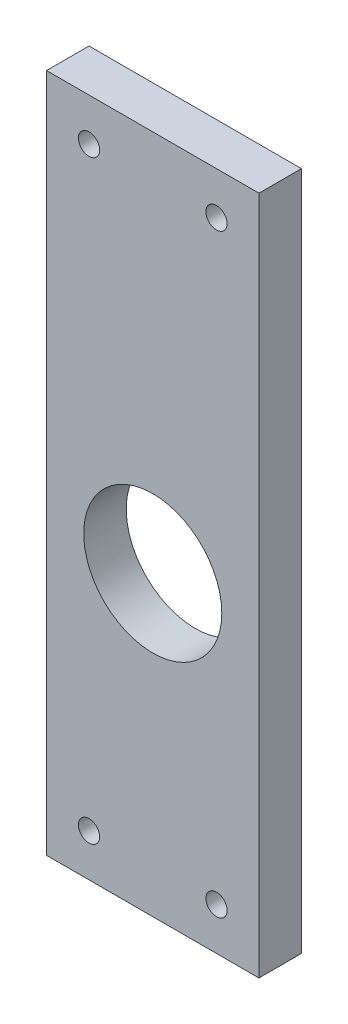
SolidWorks part; units mm, degrees
ref_plane "Front Plane" through (0, 0, 0) normal (0, 0, 1) x (1, 0, 0)
ref_plane "Top Plane" through (0, 0, 0) normal (0, 1, 0) x (1, 0, 0)
ref_plane "Right Plane" through (0, 0, 0) normal (1, 0, 0) x (0, 0, -1)
sketch "Sketch1" plane through (0, 0, 0) normal (0, 0, 1) x (1, 0, 0)
  line L1 (-31.75, 101.6) -> (31.75, 101.6)
  line L2 (-31.75, 101.6) -> (-31.75, -101.6)
  line L3 (-31.75, -101.6) -> (31.75, -101.6)
  line L4 (31.75, 101.6) -> (31.75, -101.6)
  line L5 (-31.75, 101.6) -> (31.75, -101.6) construction
  line L6 (-31.75, -101.6) -> (31.75, 101.6) construction
  point P0 (0, 0)
  dimension "D1" = 63.5
  dimension "D2" = 203.2
extrude "Boss-Extrude1" add sketch "Sketch1" along normal blind 12.7
sketch "Sketch2" plane through (0, 0, 12.7) normal (0, 0, 1) x (1, 0, 0)
  line L0 (-31.75, 101.6) -> (-31.75, -101.6) construction
  line L1 (31.75, 101.6) -> (-31.75, 101.6) construction
  circle A0 centre (-19.05, 88.9) radius 3.175
  dimension "D3" = 6.35
  dimension "D1" = 12.7
  dimension "D2" = 12.7
extrude "Cut-Extrude1" cut sketch "Sketch2" against normal through all
pattern_linear "LPattern1" count 2 spacing 38.1 along (1, 0, 0) count 2 spacing 177.8 along (0, -1, 0) of "Cut-Extrude1"
sketch "Sketch3" plane through (0, 0, 12.7) normal (0, 0, 1) x (1, 0, 0)
  line L0 (31.75, -101.6) -> (31.75, 101.6) construction
  line L1 (-31.75, -101.6) -> (31.75, -101.6) construction
  circle A0 centre (0, -12.7) radius 20.6375
  dimension "D1" = 41.275
  dimension "D3" = 88.9
  dimension "D2" = 31.75
extrude "Cut-Extrude2" cut sketch "Sketch3" against normal through all
